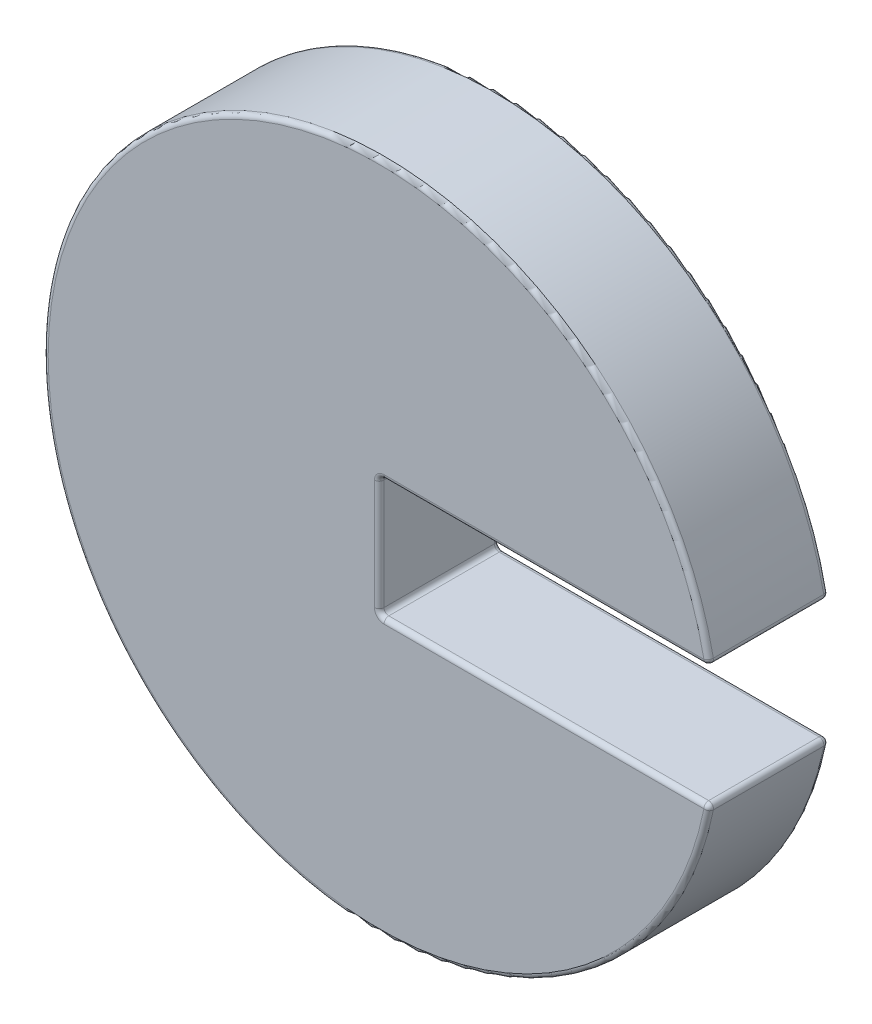
SolidWorks part; units mm, degrees
ref_plane "Plano frontal" through (0, 0, 0) normal (0, 0, 1) x (1, 0, 0)
ref_plane "Plano superior" through (0, 0, 0) normal (0, 1, 0) x (1, 0, 0)
ref_plane "Plano direito" through (0, 0, 0) normal (1, 0, 0) x (0, 0, -1)
sketch "Esboço1" plane through (0, 0, 0) normal (0, 0, 1) x (1, 0, 0)
  line L26 (-88.7344, 20.7135) -> (-80.4934, 20.7135)
  line L27 (-88.7344, 20.7135) -> (-88.7344, 18.2135)
  line L28 (-88.7344, 18.2135) -> (-80.4934, 18.2135)
  line L29 (-80.4934, 20.7135) -> (-80.4934, 18.2135)
  circle A4 centre (-88.7344, 19.4635) radius 7
  dimension "D8" = 14
  dimension "D9" = 2.5
  dimension "D10" = 1.25
extrude "Ressalto-extrusão1" add sketch "Esboço1" along normal blind 2.5 contours L26 A4 L28 L27
fillet "Filete1" radius 0.1 12 edges at (-81.8469, 20.7135, 1.25) (-81.8469, 18.2135, 1.25) (-88.7344, 18.2135, 1.25) (-88.7344, 20.7135, 1.25) (-88.7344, 19.4635, 2.5) (-85.2906, 18.2135, 2.5) (-95.7344, 19.4635, 2.5) (-85.2906, 20.7135, 2.5) (-95.7344, 19.4635, 0) (-85.2906, 18.2135, 0) (-88.7344, 19.4635, 0) (-85.2906, 20.7135, 0)
